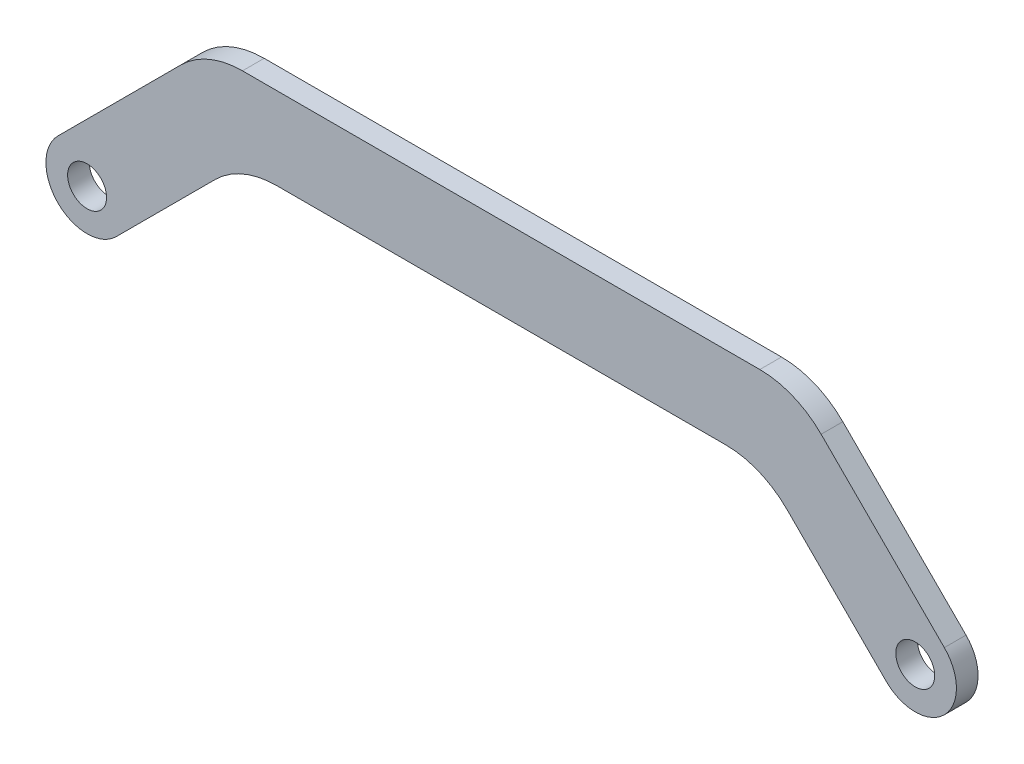
SolidWorks part; units mm, degrees
ref_plane "Front Plane" through (0, 0, 0) normal (0, 0, 1) x (1, 0, 0)
ref_plane "Top Plane" through (0, 0, 0) normal (0, 1, 0) x (1, 0, 0)
ref_plane "Right Plane" through (0, 0, 0) normal (1, 0, 0) x (0, 0, -1)
sketch "Sketch1" plane through (0, 0, 0) normal (0, 0, 1) x (1, 0, 0)
  line L0 (-6.7104, 6.7104) -> (27.5591, 40.98)
  line L1 (27.5591, 40.98) -> (163.4409, 40.98)
  line L2 (6.7104, -6.7104) -> (35.4209, 22)
  line L3 (0, 0) -> (191, 0) construction
  line L4 (95.5, 0) -> (95.5, 82.126) construction
  line L5 (35.4209, 22) -> (155.5791, 22)
  line L6 (184.2896, -6.7104) -> (155.5791, 22)
  line L7 (197.7104, 6.7104) -> (163.4409, 40.98)
  circle A0 centre (0, 0) radius 4.49
  circle A1 centre (191, 0) radius 4.49
  arc A2 (-6.7104, 6.7104) -> (6.7104, -6.7104) centre (0, 0) ccw
  arc A3 (184.2896, -6.7104) -> (197.7104, 6.7104) centre (191, 0) ccw
  point P15 (30.7866, 25.8264)
  point P16 (28.0113, 22.0098)
  point P17 (28.2237, 22)
  point P19 (95.5, 22)
  point P22 (95.5, 40.98)
  dimension "D1" = 8.98
  dimension "D2" = 8.98
  dimension "D4" = 5
  dimension "D5" = 135
  dimension "D3" = 191
  dimension "D6" = 18.98
  dimension "D7" = 22
extrude "Boss-Extrude1" add sketch "Sketch1" along normal blind 5
fillet "Fillet1" radius 20 1 edges at (27.5591, 40.98, 2.5)
fillet "Fillet2" radius 20 1 edges at (35.4209, 22, 2.5)
fillet "Fillet3" radius 20 1 edges at (163.4409, 40.98, 2.5)
fillet "Fillet4" radius 20 1 edges at (155.5791, 22, 2.5)
